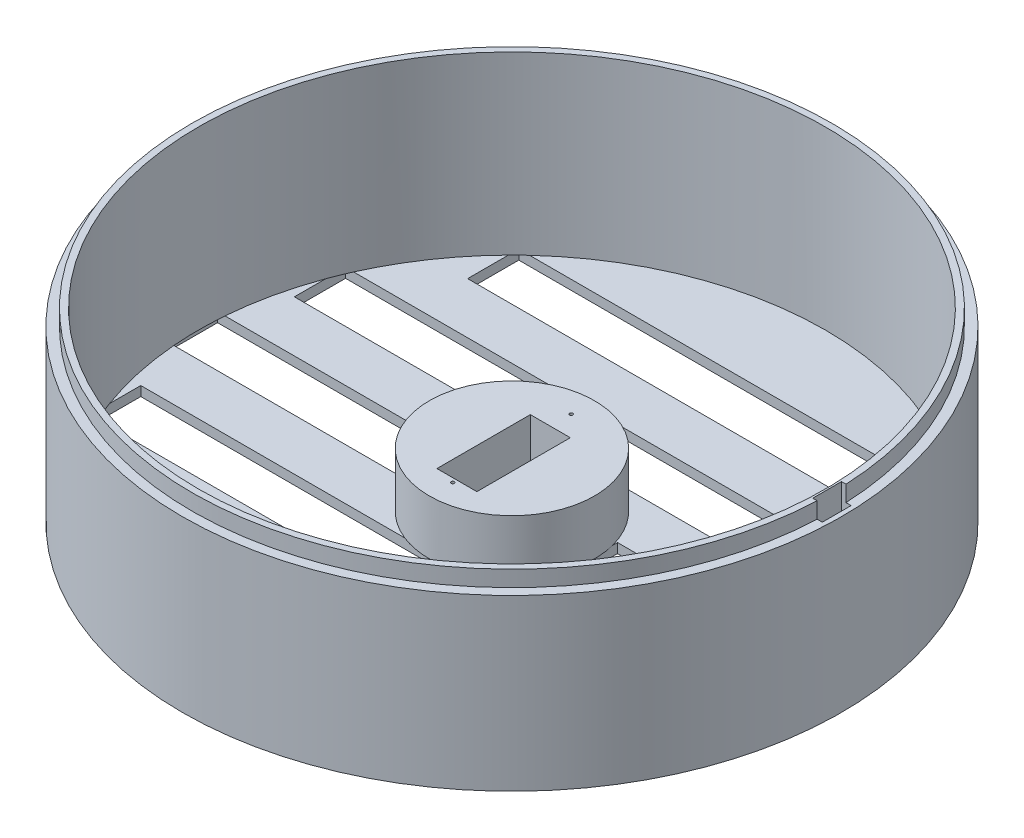
SolidWorks part; units mm, degrees
ref_plane "前视基准面" through (0, 0, 0) normal (0, 0, 1) x (1, 0, 0)
ref_plane "上视基准面" through (0, 0, 0) normal (0, 1, 0) x (1, 0, 0)
ref_plane "右视基准面" through (0, 0, 0) normal (1, 0, 0) x (0, 0, -1)
other "Configuration Table"
sketch "草图1" plane through (0, 0, 0) normal (0, 1, 0) x (1, 0, 0)
  circle A0 centre (0, 0) radius 103
  dimension "D1" = 206
extrude "凸台-拉伸1" add sketch "草图1" along normal blind 3
sketch "草图2" plane through (0, 3, 0) normal (0, 1, 0) x (1, 0, 0)
  line L1 (-12, 16) -> (12, 16)
  line L2 (-12, 16) -> (-12, -16)
  line L3 (-12, -16) -> (12, -16)
  line L4 (12, 16) -> (12, -16)
  line L5 (-15, 21) -> (15, 21)
  line L6 (-15, 21) -> (-15, -21)
  line L7 (-15, -21) -> (15, -21)
  line L8 (15, 21) -> (15, -21)
  dimension "D1" = 12
  dimension "D2" = 12
  dimension "D3" = 16
  dimension "D4" = 16
  dimension "D5" = 5
  dimension "D6" = 5
  dimension "D7" = 3
  dimension "D8" = 3
extrude "凸台-拉伸2" add sketch "草图2" along normal blind 25 contours L6 L7 L8 L5 | L2 L3 L4 L1
sketch "草图3" plane through (0, 28, 0) normal (0, 1, 0) x (1, 0, 0)
  line L0 (15, 21) -> (15, -21) construction
  circle A0 centre (0, -18.5) radius 0.5
  circle A1 centre (0, 18.5) radius 0.5
  dimension "D1" = 1
  dimension "D2" = 1
  dimension "D3" = 18.5
  dimension "D4" = 37
  dimension "D5" = 15
  dimension "D6" = 15
extrude "切除-拉伸1" cut sketch "草图3" against normal blind 25
sketch "草图4" plane through (0, 3, 0) normal (0, 1, 0) x (1, 0, 0)
  line L0 (-15, -21) -> (15, -21) construction
  line L2 (25, 0) -> (25, -8)
  line L3 (25, -8) -> (100, -8)
  line L4 (100, 0) -> (100, -8)
  line L6 (25, 0) -> (25, 8)
  line L7 (25, 8) -> (100, 8)
  line L8 (100, 0) -> (100, 8)
  dimension "D1" = 25
  dimension "D2" = 75
  dimension "D3" = 8
  dimension "D4" = 25
  dimension "D5" = 13
extrude "切除-拉伸2" cut sketch "草图4" against normal blind 25
sketch "草图5" plane through (0, 3, 0) normal (0, 1, 0) x (1, 0, 0)
  circle A0 centre (0, 0) radius 103
  circle A1 centre (0, 0) radius 100.3195
  dimension "D1" = 206
extrude "凸台-拉伸3" add sketch "草图5" along normal blind 50
sketch "草图6" plane through (0, 3, 0) normal (0, 1, 0) x (1, 0, 0)
  line L0 (25, 8) -> (25, 107.0169) construction
  line L1 (25, -8) -> (25, -4.3388) construction
  line L2 (25, -8) -> (100, -8) construction
  line L3 (25, -24) -> (92, -24) construction
  line L4 (25, -24) -> (25, -40) construction
  line L5 (25, -40) -> (92, -40) construction
  line L6 (92, -24) -> (92, -40) construction
  line L7 (-15, 21) -> (-15, -21) construction
  line L8 (25, -56) -> (69.857, -56) construction
  line L9 (25, -56) -> (25, -72) construction
  line L10 (25, -72) -> (69.857, -72) construction
  line L11 (69.857, -56) -> (69.857, -72) construction
  line L12 (25, -24) -> (-92, -24) construction
  line L14 (25, -40) -> (-92, -40) construction
  line L15 (-92, -24) -> (-92, -40) construction
  line L16 (25, -56) -> (-69.857, -56) construction
  line L18 (25, -72) -> (-69.857, -72) construction
  line L19 (-69.857, -56) -> (-69.857, -72) construction
  line L20 (-25, 8) -> (-100, 8) construction
  line L21 (-25, 8) -> (-25, -8) construction
  line L22 (-25, -8) -> (-100, -8) construction
  line L23 (-100, 8) -> (-100, -8) construction
  line L24 (-15, 21) -> (-15, -21) construction
  line L25 (25, 8) -> (25, -8) construction
  line L26 (15, 21) -> (15, -21) construction
  line L27 (100, 8) -> (25, 8) construction
  line L28 (-92, 40) -> (92, 40) construction
  line L29 (-92, 40) -> (-92, 24) construction
  line L30 (-92, 24) -> (92, 24) construction
  line L31 (92, 40) -> (92, 24) construction
  line L33 (-69.857, 72) -> (69.857, 72) construction
  line L34 (-69.857, 72) -> (-69.857, 56) construction
  line L35 (-69.857, 56) -> (69.857, 56) construction
  line L36 (69.857, 72) -> (69.857, 56) construction
  line L37 (-69.857, -56) -> (69.857, -56)
  line L38 (-69.857, -56) -> (-69.857, -72)
  line L39 (-69.857, -72) -> (69.857, -72)
  line L40 (69.857, -56) -> (69.857, -72)
  line L41 (-92, -24) -> (92, -24)
  line L42 (-92, -24) -> (-92, -40)
  line L43 (-92, -40) -> (92, -40)
  line L44 (92, -24) -> (92, -40)
  line L45 (-100, 8) -> (-25, 8)
  line L46 (-100, 8) -> (-100, -8)
  line L47 (-100, -8) -> (-25, -8)
  line L48 (-25, 8) -> (-25, -8)
  line L49 (-92, 40) -> (92, 40)
  line L50 (-92, 40) -> (-92, 24)
  line L51 (-92, 24) -> (92, 24)
  line L52 (92, 40) -> (92, 24)
  line L53 (-69.857, 72) -> (69.857, 72)
  line L54 (-69.857, 72) -> (-69.857, 56)
  line L55 (-69.857, 56) -> (69.857, 56)
  line L56 (69.857, 72) -> (69.857, 56)
  arc A0 (100, 8) -> (100, -8) centre (0, 0) ccw construction
  circle A1 centre (0, 0) radius 100.3195 construction
  point P48 (69.857, 64)
  dimension "D1" = 16
  dimension "D2" = 16
  dimension "D3" = 16
  dimension "D4" = 16
  dimension "D5" = 10
  dimension "D6" = 16
  dimension "D7" = 85
  dimension "D8" = 10
  dimension "D9" = 16
  dimension "D10" = 16
  dimension "D11" = 92
  dimension "D12" = 92
  dimension "D13" = 16
  dimension "D14" = 16
  dimension "D15" = 69.857
extrude "切除-拉伸3" cut sketch "草图6" against normal blind 50
sketch "草图7" plane through (0, 53, 0) normal (0, 1, 0) x (1, 0, 0)
  circle A0 centre (0, 0) radius 98
  circle A1 centre (0, 0) radius 103
  dimension "D1" = 206
  dimension "D2" = 196
extrude "凸台-拉伸4" add sketch "草图7" against normal blind 5
sketch "草图8" plane through (0, 53, 0) normal (0, 1, 0) x (1, 0, 0)
  circle A0 centre (0, 0) radius 100
  circle A1 centre (0, 0) radius 98
  dimension "D1" = 200
  dimension "D2" = 196
extrude "凸台-拉伸5" add sketch "草图8" along normal blind 5
sketch "草图9" plane through (0, 28, 0) normal (0, 1, 0) x (1, 0, 0)
  line L1 (-15, 21) -> (15, 21)
  line L2 (-15, 21) -> (-15, -21)
  line L3 (-15, -21) -> (15, -21)
  line L4 (15, 21) -> (15, -21)
  circle A0 centre (0, 0) radius 25.807
  line M7 (15, 21) -> (-15, 21)
  line M8 (-15, 21) -> (-15, -21)
  line M9 (-15, -21) -> (15, -21)
  line M10 (15, -21) -> (15, 21)
extrude "凸台-拉伸6" add sketch "草图9" against normal blind 25 contours A0 M10 | A0 M7 | A0 M8 | A0 M9
sketch "草图10" plane through (0, 28, 0) normal (0, 1, 0) x (1, 0, 0)
  line L0 (-6.25, 12) -> (-12, 16) construction
  line L1 (-6.25, 12) -> (6.25, 12)
  line L2 (-6.25, 12) -> (-6.25, -12)
  line L3 (-6.25, -12) -> (6.25, -12)
  line L4 (6.25, 12) -> (6.25, -12)
  line L5 (-12, 16) -> (12, 16)
  line L6 (-12, 16) -> (-12, -16)
  line L7 (-12, -16) -> (12, -16)
  line L8 (12, 16) -> (12, -16)
  line L9 (6.25, 12) -> (12, 16) construction
  line L10 (-6.25, -12) -> (-12, -16) construction
  line L11 (6.25, -12) -> (12, -16) construction
  dimension "D1" = 12.5
  dimension "D2" = 24
extrude "凸台-拉伸7" add sketch "草图10" against normal blind 25
sketch "草图11" plane through (0, 28, 0) normal (0, 1, 0) x (1, 0, 0)
  line L1 (-6.25, 12) -> (6.25, 12)
  line L2 (-6.25, 12) -> (-6.25, -12)
  line L3 (-6.25, -12) -> (6.25, -12)
  line L4 (6.25, 12) -> (6.25, -12)
  circle A0 centre (0, 0) radius 25.807
extrude "切除-拉伸4" cut sketch "草图11" against normal blind 8
sketch "草图12" plane through (0, 0, 0) normal (0, -1, 0) x (1, 0, 0)
  line L0 (6.25, -12) -> (-6.25, -12) construction
  line L1 (-6.25, 12) -> (6.25, 12)
  line L2 (-6.25, 12) -> (-6.25, -12)
  line L3 (-6.25, -12) -> (6.25, -12)
  line L4 (6.25, 12) -> (6.25, -12)
  line L5 (6.25, 12) -> (6.25, -12) construction
extrude "切除-拉伸5" cut sketch "草图12" against normal blind 8
sketch "草图13" plane through (0, 20, 0) normal (0, 1, 0) x (1, 0, 0)
  line L1 (-6.25, -12) -> (6.25, -12)
  line L2 (-6.25, -12) -> (-6.25, -17.2)
  line L3 (-6.25, -17.2) -> (6.25, -17.2)
  line L4 (6.25, -12) -> (6.25, -17.2)
  dimension "D1" = 5.2
extrude "切除-拉伸6" cut sketch "草图13" against normal blind 100
sketch "草图14" plane through (0, 3, 0) normal (0, 1, 0) x (1, 0, 0)
  circle A0 centre (0, 0) radius 98
  circle A1 centre (0, 0) radius 103
  dimension "D1" = 196
  dimension "D2" = 206
extrude "凸台-拉伸9" add sketch "草图14" along normal blind 50
sketch "草图15" plane through (0, 58, 0) normal (0, 1, 0) x (1, 0, 0)
  line L0 (0, 0) -> (183.1966, 0) construction
  line L2 (98.5, 4.5) -> (101.5, 4.5)
  line L3 (98.5, 4.5) -> (98.5, -4.5)
  line L4 (98.5, -4.5) -> (101.5, -4.5)
  line L5 (101.5, 4.5) -> (101.5, -4.5)
  circle A0 centre (0, 0) radius 103 construction
  dimension "D4" = 101.5
  dimension "D1" = 9
  dimension "D2" = 3
  dimension "D3" = 4.5
extrude "切除-拉伸7" cut sketch "草图15" against normal blind 70
